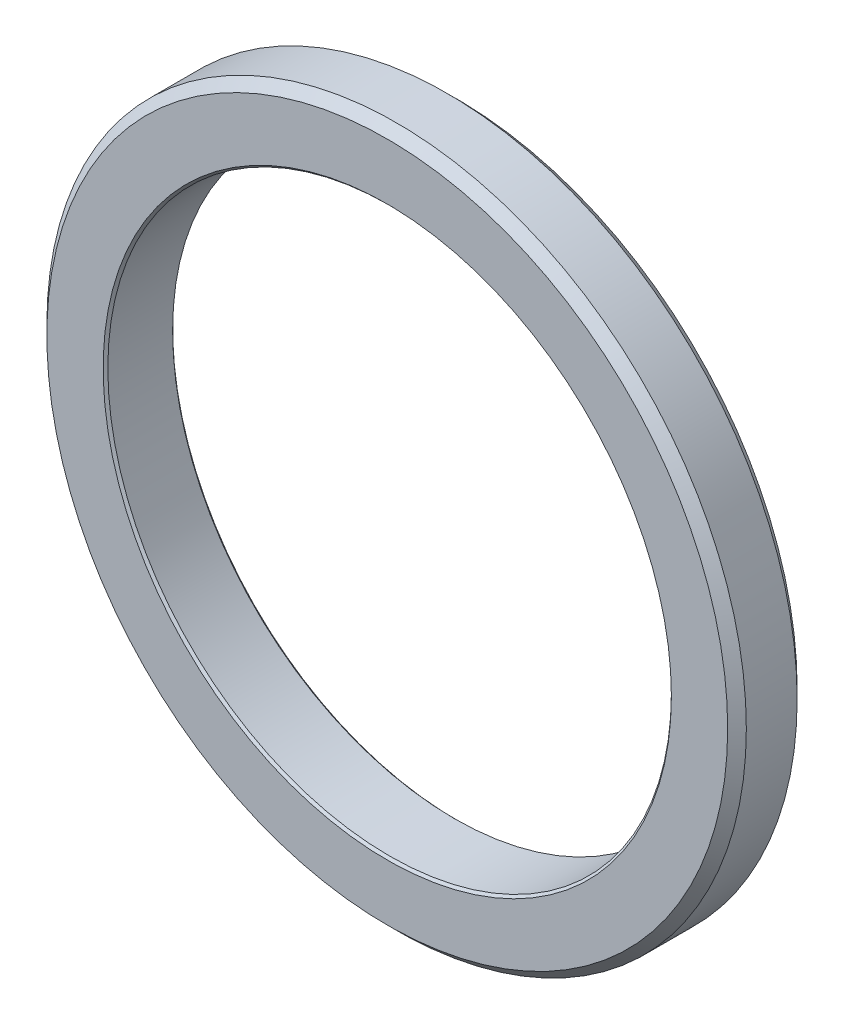
SolidWorks part; units mm, degrees
material "PB01 (C90710) Bronze"
ref_plane "Front Plane" through (0, 0, 0) normal (0, 0, 1) x (1, 0, 0)
ref_plane "Top Plane" through (0, 0, 0) normal (0, 1, 0) x (1, 0, 0)
ref_plane "Right Plane" through (0, 0, 0) normal (1, 0, 0) x (0, 0, -1)
sketch "Sketch1" plane through (0, 0, 0) normal (1, 0, 0) x (0, 0, -1)
  line L0 (0, 0) -> (41.4438, 0) construction
  line L1 (0, 30.475) -> (0.25, 30.225)
  line L2 (1, 37.515) -> (6.45, 37.515)
  line L3 (0, 36.515) -> (0, 30.475)
  line L4 (0.25, 30.225) -> (7.2, 30.225)
  line L5 (7.45, 36.515) -> (7.45, 30.475)
  line L6 (7.2, 30.225) -> (7.45, 30.475)
  line L7 (0, 36.515) -> (1, 37.515)
  line L8 (6.45, 37.515) -> (7.45, 36.515)
  point P3 (0, 37.515)
  point P4 (7.45, 30.225)
  point P5 (0, 30.225)
  point P6 (7.45, 37.515)
  dimension "D1" = 60.45
  dimension "D2" = 75.03
  dimension "D3" = 7.45
revolve "Revolve1" add sketch "Sketch1" angle 360 about L0
